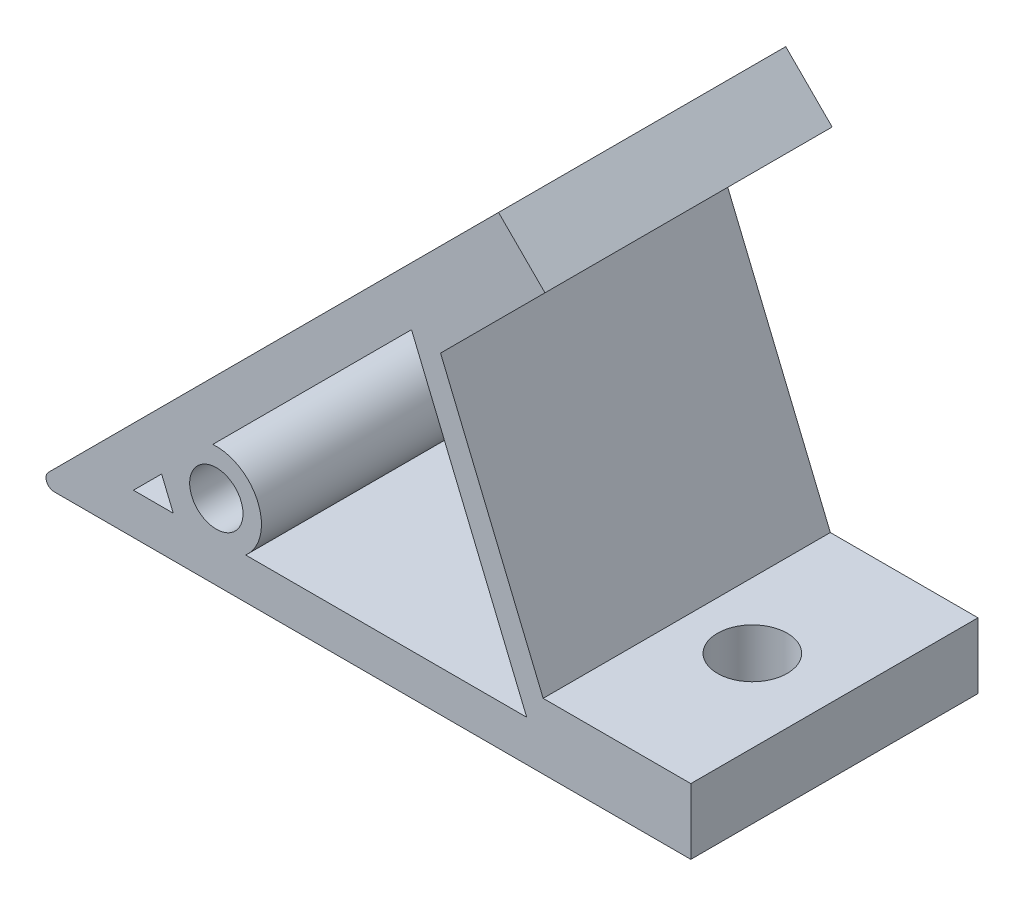
SolidWorks part; units mm, degrees
ref_plane "前视基准面" through (0, 0, 0) normal (0, 0, 1) x (1, 0, 0)
ref_plane "上视基准面" through (0, 0, 0) normal (0, 1, 0) x (1, 0, 0)
ref_plane "右视基准面" through (0, 0, 0) normal (1, 0, 0) x (0, 0, -1)
sketch "草图1" plane through (0, 0, 0) normal (0, 0, 1) x (1, 0, 0)
  line B0 (-77.5858, 0) -> (0, 0)
  line B1 (-67.9289, 5) -> (-63.0745, 5)
  line B2 (-54.2575, 5) -> (-20, 5)
  line B3 (-17.9955, 8) -> (0, 8)
  line B4 (-78.2929, 1.7071) -> (-23.4315, 56.5685)
  line B5 (-67.9289, 5) -> (-64.4963, 8.4326)
  line B6 (-58.2617, 14.6672) -> (-34.0381, 38.8909)
  line B7 (-30.4993, 38.187) -> (-17.7746, 50.9117)
  line B8 (0, 0) -> (0, 8)
  line B9 (-17.7746, 50.9117) -> (-23.4315, 56.5685)
  line B10 (-20, 5) -> (-34.0381, 38.8909)
  line B11 (-17.9955, 8) -> (-30.4993, 38.187)
  line B12 (-63.0745, 5) -> (-64.4963, 8.4326)
  arc B13 (-78.2929, 1.7071) -> (-77.5858, 0) centre (-77.5858, 1) ccw
  circle B14 centre (-57.8269, 9.1844) radius 3.25
  arc B15 (-54.2575, 5) -> (-58.2617, 14.6672) centre (-57.8269, 9.1844) ccw
sketch_block_instance "A$C18907C9D-1"
sketch_block "A$C18907C9D"
extrude "凸台-拉伸1" add sketch "草图1" along normal mid plane 35
sketch "草图3" plane through (0, 8, 0) normal (0, 1, 0) x (1, 0, 0)
  line L0 (0, -17.5) -> (0, 17.5) construction
  circle A0 centre (-10, 0) radius 4.25
  dimension "D1" = 10
extrude "切除-拉伸1" cut sketch "草图3" against normal blind 17
sketch "草图4" plane through (-12.5317, -5.1908, 0) normal (0.9239, 0.3827, 0) x (0, 0, -1)
  line L0 (-17.5, 30.6147) -> (17.5, 30.6147) construction
  line L1 (-17.5, 14.2776) -> (-17.5, 46.9517) construction
  line L2 (17.5, 14.2776) -> (17.5, 46.9517) construction
ref_plane "基准面2" through (-11.7157, 28.2843, 0) normal (-0.3827, 0.9239, 0) x (0.9239, 0.3827, 0)
mirror "镜向1" about plane through (-11.7157, 28.2843, 0) normal (-0.3827, 0.9239, 0) of "切除-拉伸1"
